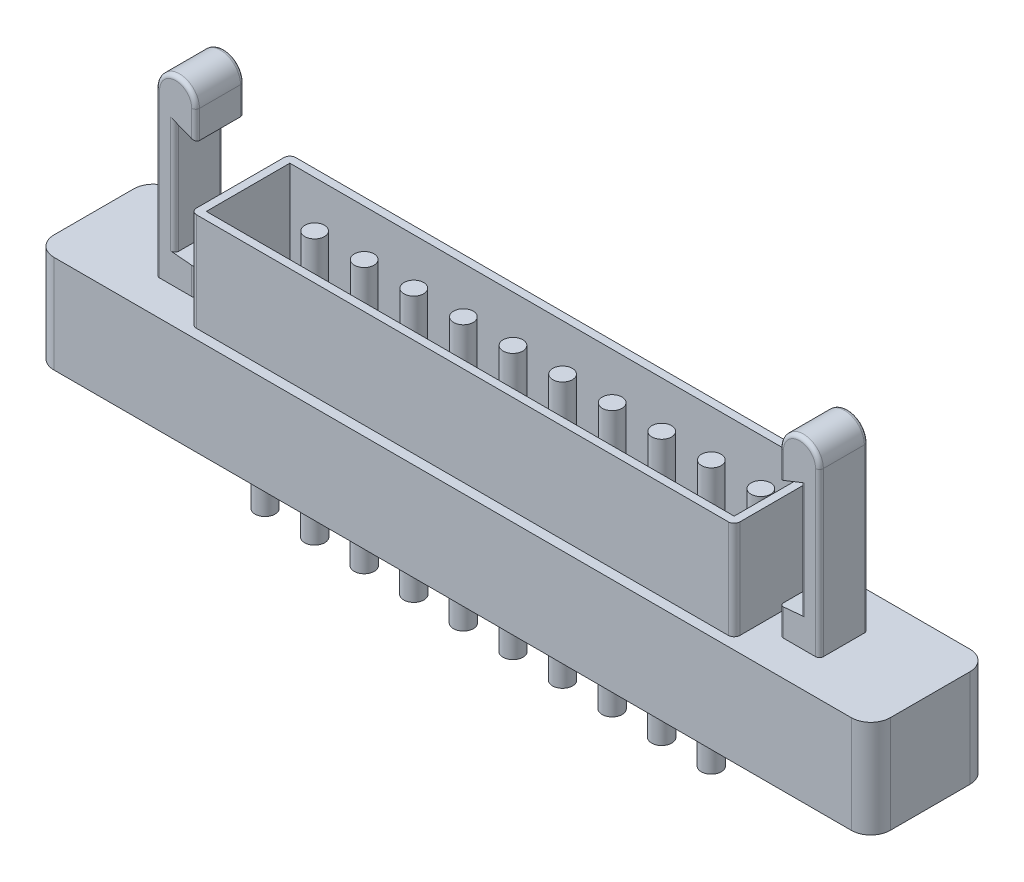
SolidWorks part; units mm, degrees
ref_plane "Спереди" through (0, 0, 0) normal (0, 0, 1) x (1, 0, 0)
ref_plane "Сверху" through (0, 0, 0) normal (0, 1, 0) x (1, 0, 0)
ref_plane "Справа" through (0, 0, 0) normal (1, 0, 0) x (0, 0, -1)
sketch "Эскиз2" plane through (0, 0, 0) normal (0, 0, 1) x (1, 0, 0)
  line L0 (20.62, 7.4474) -> (20.62, -4.0545) construction
  line L1 (0, 0) -> (41.24, 0)
  line L2 (0, 0) -> (0, 2.54)
  line L3 (0, 7.62) -> (41.24, 7.62)
  line L4 (41.24, 0) -> (41.24, 2.54)
  line L5 (1.57, 5) -> (39.67, 5)
  line L6 (1.57, 5) -> (1.57, 6)
  line L7 (1.57, 6) -> (39.67, 6)
  line L8 (39.67, 5) -> (39.67, 6)
  line L9 (41.24, 3.34) -> (41.24, 7.62)
  line L10 (0, 3.34) -> (0.3, 3.34)
  line L12 (0, 2.54) -> (0.3, 2.54)
  line L13 (0.3, 3.34) -> (0.3, 2.54)
  line L14 (41.24, 3.34) -> (40.94, 3.34)
  line L15 (0, 3.34) -> (0, 7.62)
  line L16 (41.24, 2.54) -> (40.94, 2.54)
  line L17 (40.94, 3.34) -> (40.94, 2.54)
  dimension "D1" = 41.24
  dimension "D2" = 7.62
  dimension "D3" = 1
  dimension "D4" = 5
  dimension "D5" = 38.1
  dimension "D6" = 0.3
  dimension "D7" = 0.8
  dimension "D8" = 0.8
  dimension "D9" = 0.3
  dimension "D10" = 2.54
  dimension "D11" = 2.54
extrude "Вытянуть1" add sketch "Эскиз2" along normal blind 5.08
sketch "Эскиз3" plane through (0, 0, 0) normal (0, -1, 0) x (1, 0, 0)
  line L0 (0, 0) -> (41.24, 0) construction
  line L1 (0, 5.08) -> (0, 0) construction
  circle A0 centre (2.54, 3.81) radius 0.5141
  circle A1 centre (2.54, 1.27) radius 0.5024
  dimension "D1" = 2.54
  dimension "D2" = 1.27
  dimension "D3" = 2.54
  dimension "D4" = 2.54
extrude "Вытянуть2" add sketch "Эскиз3" along normal blind 2.5
pattern_linear "Линейный массив1" count 10 spacing 2.54 along (1, 0, 0) of "Вытянуть2"
sketch "Эскиз4" plane through (0, 7.62, 0) normal (0, 1, 0) x (-1, 0, 0)
  line L1 (-43.0607, -1.7915) -> (1.138, -1.7915)
  line L2 (-43.0607, -1.7915) -> (-43.0607, 6.6797)
  line L3 (-43.0607, 6.6797) -> (1.138, 6.6797)
  line L4 (1.138, -1.7915) -> (1.138, 6.6797)
extrude "Вырез-Вытянуть1" cut sketch "Эскиз4" against normal up to surface (5.08 mm away) up to face at (41.09, 2.54, 2.54)
sketch "Эскиз5" plane through (0, 2.54, 0) normal (0, 1, 0) x (-1, 0, 0)
  circle A1 centre (-15.24, 1.27) radius 0.5024
  circle A2 centre (-15.24, 1.27) radius 0.5024
  circle A3 centre (-15.24, 3.81) radius 0.5141
  circle A4 centre (-15.24, 3.81) radius 0.5141
  circle A5 centre (-12.7, 3.81) radius 0.5141 construction
  circle A6 centre (-10.16, 3.81) radius 0.5141 construction
  circle A7 centre (-7.62, 3.81) radius 0.5141 construction
  circle A8 centre (-5.08, 3.81) radius 0.5141 construction
  circle A9 centre (-2.54, 3.81) radius 0.5141 construction
  circle A10 centre (-2.54, 1.27) radius 0.5024 construction
  circle A11 centre (-5.08, 1.27) radius 0.5024 construction
  circle A12 centre (-7.62, 1.27) radius 0.5024 construction
  circle A13 centre (-10.16, 1.27) radius 0.5024 construction
  circle A14 centre (-12.7, 1.27) radius 0.5024 construction
  circle A15 centre (-17.78, 1.27) radius 0.5024
  circle A16 centre (-17.78, 1.27) radius 0.5024
  circle A17 centre (-17.78, 3.81) radius 0.5141
  circle A18 centre (-17.78, 3.81) radius 0.5141
  circle A19 centre (-20.32, 1.27) radius 0.5024
  circle A20 centre (-20.32, 1.27) radius 0.5024
  circle A21 centre (-20.32, 3.81) radius 0.5141
  circle A22 centre (-20.32, 3.81) radius 0.5141
  circle A23 centre (-22.86, 1.27) radius 0.5024
  circle A24 centre (-22.86, 1.27) radius 0.5024
  circle A25 centre (-12.7, 3.81) radius 0.5141
  circle A26 centre (-10.16, 3.81) radius 0.5141
  circle A27 centre (-7.62, 3.81) radius 0.5141
  circle A28 centre (-5.08, 3.81) radius 0.5141
  circle A29 centre (-2.54, 3.81) radius 0.5141
  circle A30 centre (-2.54, 1.27) radius 0.5024
  circle A31 centre (-5.08, 1.27) radius 0.5024
  circle A32 centre (-7.62, 1.27) radius 0.5024
  circle A33 centre (-10.16, 1.27) radius 0.5024
  circle A34 centre (-12.7, 1.27) radius 0.5024
  circle A35 centre (-22.86, 3.81) radius 0.5141
  circle A36 centre (-22.86, 3.81) radius 0.5141
  circle A37 centre (-25.4, 1.27) radius 0.5024
  circle A38 centre (-25.4, 1.27) radius 0.5024
  circle A39 centre (-25.4, 3.81) radius 0.5141
  circle A40 centre (-25.4, 3.81) radius 0.5141
  dimension "D1" = 0
  dimension "D2" = 0
  dimension "D3" = 0
  dimension "D4" = 0
  dimension "D5" = 0
  dimension "D6" = 0
  dimension "D7" = 0
  dimension "D8" = 0
  dimension "D9" = 0
  dimension "D10" = 0
extrude "Вытянуть3" add sketch "Эскиз5" along normal blind 6
sketch "Эскиз6" plane through (0, 0, 0) normal (0, -1, 0) x (1, 0, 0)
  line L0 (0, 5.08) -> (41.24, 5.08) construction
  line L1 (-5, 5.58) -> (46.24, 5.58)
  line L2 (-5, 5.58) -> (-5, -0.5)
  line L3 (-5, -0.5) -> (46.24, -0.5)
  line L4 (46.24, 5.58) -> (46.24, -0.5)
  line L5 (0, 0) -> (41.24, 0) construction
  line L6 (41.24, 5.08) -> (41.24, 0) construction
  line L7 (0, 5.08) -> (0, 0) construction
  dimension "D1" = 0.5
  dimension "D2" = 0.5
  dimension "D3" = 5
  dimension "D4" = 5
extrude "Вытянуть4" add sketch "Эскиз6" against normal blind 2.4
sketch "Эскиз7" plane through (0, 2.54, 0) normal (0, 1, 0) x (-1, 0, 0)
  line L0 (-27.44, 4.68) -> (-27.44, 0.4)
  line L1 (-0.4, 4.68) -> (-27.44, 4.68)
  line L2 (-0.4, 4.68) -> (-0.4, 0.4)
  line L3 (-0.4, 0.4) -> (-27.44, 0.4)
  line L4 (-41.24, 0) -> (0, 0)
  line L5 (-27.84, 0) -> (0, 0)
  line L6 (0, 0) -> (0, 5.08)
  line L7 (0, 0) -> (0, 5.08)
  line L8 (0, 5.08) -> (-41.24, 5.08)
  line L9 (0, 5.08) -> (-27.84, 5.08)
  line L10 (-41.24, 5.08) -> (-41.24, 0)
  line L13 (-27.84, 5.08) -> (-27.84, 0)
  circle A0 centre (-2.54, 3.81) radius 0.5141 construction
  circle A1 centre (-25.4, 1.27) radius 0.5024 construction
  dimension "D2" = 2.14
  dimension "D3" = 2.04
  dimension "D7" = 0.4
  dimension "D1" = 0
extrude "Вытянуть6" add sketch "Эскиз7" along normal blind 7.5
sketch "Эскиз8" plane through (0, 2.4, 0) normal (0, 1, 0) x (-1, 0, 0)
  line L4 (5, -0.5) -> (5, 5.58)
  line L5 (5, 5.58) -> (-46.24, 5.58)
  line L6 (-46.24, 5.58) -> (-46.24, -0.5)
  line L7 (-46.24, -0.5) -> (5, -0.5)
  line L8 (5, -0.5) -> (5, 5.58)
  line L9 (5, 5.58) -> (-46.24, 5.58)
  line L10 (-46.24, 5.58) -> (-46.24, -0.5)
  line L11 (-46.24, -0.5) -> (5, -0.5)
  dimension "D1" = 0
extrude "Вытянуть7" add sketch "Эскиз8" along normal blind 2.6
ref_plane "Плоскость1" through (0, 0, 2.54) normal (0, 0, 1) x (1, 0, 0)
sketch "Эскиз9" plane through (0, 0, 2.54) normal (0, 0, 1) x (1, 0, 0)
  line L0 (13.92, 15.9279) -> (13.92, 2.2251) construction
  line L1 (-3.08, 2.2251) -> (-1.0385, 2.2251)
  line L2 (-3.08, 2.2251) -> (-3.08, 13.3476)
  line L3 (0, 10.04) -> (0, 5) construction
  line L4 (-1.0385, 2.2251) -> (-1.0385, 6.3698)
  line L5 (27.84, 10.04) -> (27.84, 5) construction
  line L6 (28.8785, 11.9211) -> (28.8785, 13.3476)
  line L7 (29.9526, 6.4647) -> (28.8785, 6.3698)
  line L8 (29.9526, 12.3474) -> (29.9526, 6.4647)
  line L11 (-1.0385, 11.9211) -> (-2.1126, 12.3474)
  line L12 (-2.1126, 12.3474) -> (-2.1126, 6.4647)
  line L13 (-2.1126, 6.4647) -> (-1.0385, 6.3698)
  line L14 (28.8785, 11.9211) -> (29.9526, 12.3474)
  line L15 (28.8785, 2.2251) -> (28.8785, 6.3698)
  line L16 (30.92, 2.2251) -> (30.92, 13.3476)
  line L17 (30.92, 2.2251) -> (28.8785, 2.2251)
  line L18 (-1.0385, 11.9211) -> (-1.0385, 13.3476)
  arc A0 (-3.08, 13.3476) -> (-1.0385, 13.3476) centre (-2.0592, 13.3476) cw
  arc A1 (30.92, 13.3476) -> (28.8785, 13.3476) centre (29.8992, 13.3476) ccw
  dimension "D1" = 34
extrude "Вытянуть8" add sketch "Эскиз9" along normal blind 1.25 and the other way blind 1.25
fillet "Скругление1" radius 0.3 4 edges at (0, 7.52, 0) (0, 7.52, 5.08) (27.84, 7.52, 0) (27.84, 7.52, 5.08)
fillet "Скругление2" radius 0.2 20 edges at (-1.0385, 12.6344, 1.29) (-2.0592, 14.3684, 1.29) (-1.0385, 12.6344, 3.79) (-2.0592, 14.3684, 3.79) (-2.1126, 9.4061, 3.79) (-2.1126, 9.4061, 1.29) (-3.08, 9.1738, 1.29) (-3.08, 9.1738, 3.79) (28.8785, 12.6344, 1.29) (29.8992, 14.3684, 1.29) (28.8785, 12.6344, 3.79) (29.8992, 14.3684, 3.79) (29.9526, 9.4061, 1.29) (29.9526, 9.4061, 3.79) (30.92, 9.1738, 1.29) (30.92, 9.1738, 3.79) (-1.0385, 5.6849, 3.79) (-1.0385, 5.6849, 1.29) (28.8785, 5.6849, 3.79) (28.8785, 5.6849, 1.29)
sketch "Эскиз10" plane through (46.24, 0, 0) normal (1, 0, 0) x (0, 0, -1)
  line L4 (-5.58, 0) -> (0.5, 0)
  line L5 (0.5, 0) -> (0.5, 5)
  line L6 (0.5, 5) -> (-5.58, 5)
  line L7 (-5.58, 5) -> (-5.58, 0)
  line L8 (-5.58, 0) -> (0.5, 0)
  line L9 (0.5, 0) -> (0.5, 5)
  line L10 (0.5, 5) -> (-5.58, 5)
  line L11 (-5.58, 5) -> (-5.58, 0)
  dimension "D1" = 0
extrude "Вырез-Вытянуть2" cut sketch "Эскиз10" against normal offset from surface (13.4 mm away) 5 up to face at (27.84, 7.52, 2.54)
sketch "Эскиз11" plane through (32.84, 0, 0) normal (1, 0, 0) x (0, 0, -1)
  line L4 (-5.58, 5) -> (-5.58, 0)
  line L5 (-5.58, 0) -> (0.5, 0)
  line L6 (0.5, 0) -> (0.5, 5)
  line L7 (0.5, 5) -> (-5.58, 5)
  line L8 (-5.58, 5) -> (-5.58, 0)
  line L9 (-5.58, 0) -> (0.5, 0)
  line L10 (0.5, 0) -> (0.5, 5)
  line L11 (0.5, 5) -> (-5.58, 5)
  dimension "D1" = 0
extrude "Вытянуть9" add sketch "Эскиз11" along normal blind 2.5
sketch "Эскиз12" plane through (-5, 0, 0) normal (-1, 0, 0) x (0, 0, 1)
  line L4 (-0.5, 0) -> (5.58, 0)
  line L5 (5.58, 0) -> (5.58, 5)
  line L6 (5.58, 5) -> (-0.5, 5)
  line L7 (-0.5, 5) -> (-0.5, 0)
  line L8 (-0.5, 0) -> (5.58, 0)
  line L9 (5.58, 0) -> (5.58, 5)
  line L10 (5.58, 5) -> (-0.5, 5)
  line L11 (-0.5, 5) -> (-0.5, 0)
  dimension "D1" = 0
extrude "Вытянуть10" add sketch "Эскиз12" along normal blind 2.5
fillet "Скругление3" radius 1 4 edges at (35.34, 2.5, 5.58) (35.34, 2.5, -0.5) (-7.5, 2.5, -0.5) (-7.5, 2.5, 5.58)
